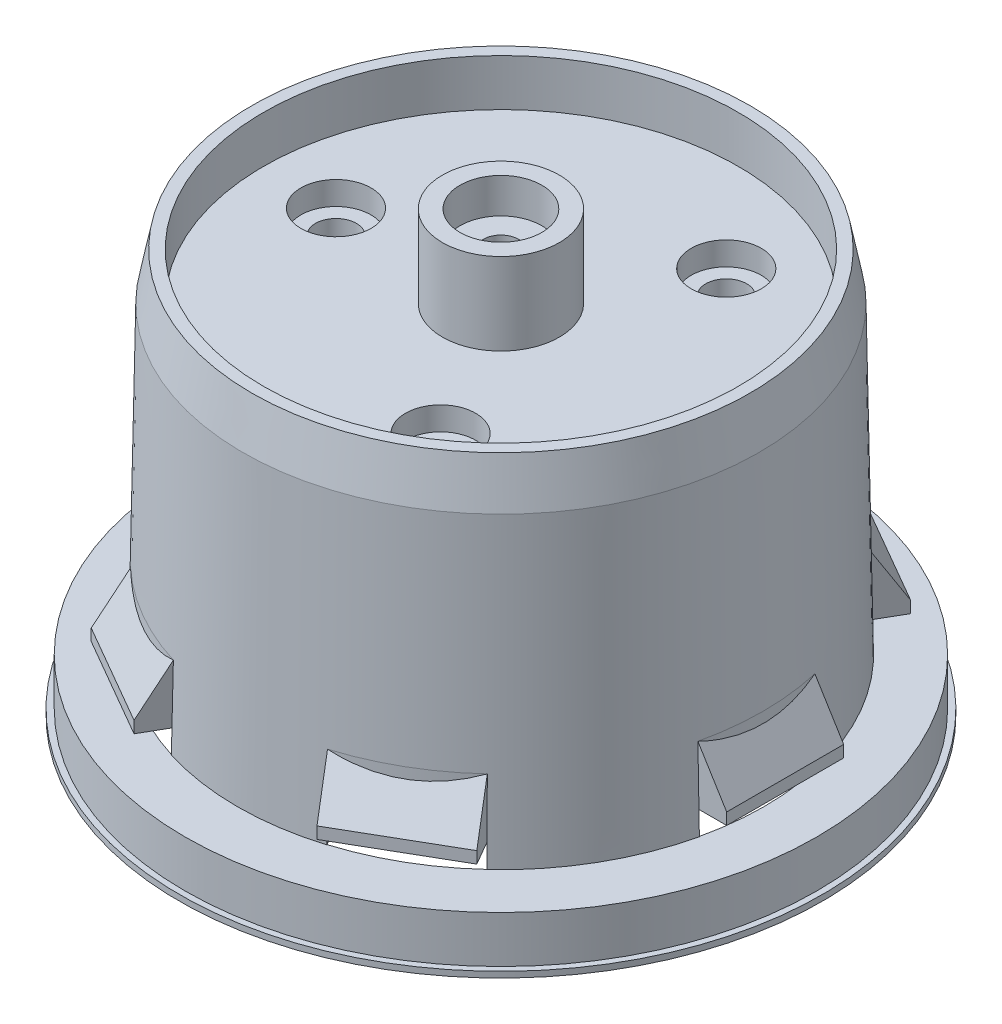
SolidWorks part; units mm, degrees
material "ABS PC"
ref_plane "Piano frontale" through (0, 0, 0) normal (0, 0, 1) x (1, 0, 0)
ref_plane "Piano superiore" through (0, 0, 0) normal (0, 1, 0) x (1, 0, 0)
ref_plane "Piano destro" through (0, 0, 0) normal (1, 0, 0) x (0, 0, -1)
sketch "Schizzo1" plane through (0, 0, 0) normal (0, 1, 0) x (1, 0, 0)
  circle A0 centre (0, 0) radius 22
  dimension "D1" = 44
extrude "Estrusione-Estrusione1" add sketch "Schizzo1" along normal blind 30
draft "Sformo1" type of draft neutral plane draft angle 1 faces to draft 1 face at (0, 30, 22) neutral plane through (0, 30, 0) neutral plane normal (0, 1, 0) parameters "D1"=1
chamfer "Smusso1" distance 4 angle 10 1 edges at (0, 30, 22)
sketch "Schizzo2" plane through (0, 30, 0) normal (0, 1, 0) x (1, 0, 0)
  circle A0 centre (0, 0) radius 20.2924
  circle A1 centre (0, 0) radius 21.2924 construction
  dimension "D1" = 1
extrude "Taglio-Estrusione1" cut sketch "Schizzo2" against normal blind 4
shell "Svuota1" thickness 3
sketch "Schizzo4" plane through (0, 26, 0) normal (0, 1, 0) x (1, 0, 0)
  line L0 (-17.5737, 10.1462) -> (17.5737, -10.1462) construction
  line L1 (17.5737, 10.1462) -> (-17.5737, -10.1462) construction
  line L2 (0, -20.2924) -> (0, 20.2924) construction
  line L3 (0, 0) -> (10.1462, 17.5737) construction
  circle A0 centre (0, 0) radius 20.2924 construction
  circle A1 centre (0, 0) radius 20.2924 construction
  circle A3 centre (7.05, 12.211) radius 3
  point P7 (0, 0)
  point P13 (0, 0)
  point P17 (0, 0)
  dimension "D5" = 6
  dimension "D1" = 60
  dimension "D2" = 60
  dimension "D3" = 30
  dimension "D4" = 14.1
extrude "Taglio-Estrusione2" cut sketch "Schizzo4" against normal blind 2
sketch "Schizzo5" plane through (0, 24, 0) normal (0, 1, 0) x (1, 0, 0)
  circle A0 centre (7.05, 12.211) radius 1.75
  dimension "D1" = 3.5
extrude "Taglio-Estrusione3" cut sketch "Schizzo5" against normal through all
pattern_circular "RipetizioneCircolare1" count 3 over 360 about axis through (0, 0, 0) along (0, 1, 0) of "Taglio-Estrusione3", "Taglio-Estrusione2"
sketch "Schizzo3" plane through (0, 26, 0) normal (0, 1, 0) x (1, 0, 0)
  circle A0 centre (0, 0) radius 5
  dimension "D1" = 10
extrude "Estrusione-Estrusione2" add sketch "Schizzo3" along normal blind 7
sketch "Schizzo6" plane through (0, 33, 0) normal (0, 1, 0) x (1, 0, 0)
  circle A0 centre (0, 0) radius 3.5
  dimension "D1" = 7
extrude "Taglio-Estrusione5" cut sketch "Schizzo6" against normal blind 3
sketch "Schizzo8" plane through (0, 23, 0) normal (0, -1, 0) x (1, 0, 0)
  line L0 (-17.5737, -10.1462) -> (17.5737, 10.1462) construction
  line L1 (0, 20.2924) -> (0, -20.2924) construction
  line L2 (17.5737, -10.1462) -> (-17.5737, 10.1462) construction
  line L3 (-17.5737, -10.1462) -> (17.5737, 10.1462)
  line L4 (0, 20.2924) -> (0, -20.2924)
  line L5 (17.5737, -10.1462) -> (-17.5737, 10.1462)
extrude "Estrusione-Sottile1" add sketch "Schizzo8" along normal blind 8 thin thin type mid plane wall 1
sketch "Schizzo7" plane through (0, 30, 0) normal (0, 1, 0) x (1, 0, 0)
  circle A0 centre (0, 0) radius 2.5
  circle A1 centre (0, 0) radius 1.5
  dimension "D1" = 5
  dimension "D2" = 3
extrude "Estrusione-Estrusione5" add sketch "Schizzo7" against normal offset from surface (17 mm away) 2 up to face at (0, 15, 0) offset beyond the face yes
sketch "Schizzo10" plane through (0, 30, 0) normal (0, 1, 0) x (1, 0, 0)
  circle A0 centre (0, 0) radius 1.5 construction
  circle A1 centre (0, 0) radius 1.5
extrude "Taglio-Estrusione7" cut sketch "Schizzo10" against normal through all
sketch "Schizzo11" plane through (0, 15, 0) normal (0, -1, 0) x (1, 0, 0)
  line L1 (-0.5, -2.4495) -> (-0.5, -19.2549) construction
  line L2 (0.5, -2.4495) -> (0.5, -19.1152) construction
  line L4 (0.5, -2.4495) -> (0.5, -19.2549) construction
  line L5 (-0.5, -10.8522) -> (0.5, -10.8522) construction
  line L6 (-0.5, -2.4495) -> (-0.5, -19.1152) construction
  circle A0 centre (0, -10.8522) radius 0.75
  point P2 (0.5, -10.8522)
  point P4 (-0.5, -10.8522)
  dimension "D1" = 1.5
extrude "Estrusione-Estrusione6" add sketch "Schizzo11" against normal up to surface (8 mm away) up to face at (-5.0997, 23, -8.8329)
pattern_circular "RipetizioneCircolare2" count 6 over 360 about axis through (0, 0, 0) along (0, 1, 0) of "Estrusione-Estrusione6"
sketch "Schizzo12" plane through (0, 23, 0) normal (0, -1, 0) x (1, 0, 0)
  circle A0 centre (7.05, -12.211) radius 3.5
  circle A1 centre (7.05, -12.211) radius 1.75 construction
  circle A2 centre (7.05, -12.211) radius 1.75
  dimension "D1" = 7
extrude "Estrusione-Estrusione7" add sketch "Schizzo12" along normal blind 5
sketch "Schizzo13" plane through (0, 18, 0) normal (0, -1, 0) x (1, 0, 0)
  circle A0 centre (7.05, -12.211) radius 3
  circle A1 centre (7.05, -12.211) radius 3.5 construction
  dimension "D1" = 0.5
extrude "Taglio-Estrusione8" cut sketch "Schizzo13" against normal blind 1.5
pattern_circular "RipetizioneCircolare3" count 3 over 360 about axis through (0, 0, 0) along (0, 1, 0) of "Taglio-Estrusione8", "Estrusione-Estrusione7"
sketch "Schizzo14" plane through (0, 0, 0) normal (0, -1, 0) x (1, 0, 0)
  circle A0 centre (0, 0) radius 27
  circle A1 centre (0, 0) radius 22.5
  dimension "D1" = 54
  dimension "D2" = 45
extrude "Estrusione-Estrusione8" add sketch "Schizzo14" along normal blind 4
sketch "Schizzo16" plane through (0, -4, 0) normal (0, -1, 0) x (1, 0, 0)
  circle A0 centre (0, 0) radius 27.5
  circle A1 centre (0, 0) radius 26.5
  dimension "D1" = 53
  dimension "D2" = 55
extrude "Estrusione-Estrusione9" add sketch "Schizzo16" along normal blind 0.5
ref_plane "Piano1" through (11.1484, 0, -19.3095) normal (0.5, 0, -0.866) x (0, 1, 0)
sketch "Schizzo17" plane through (11.1484, 0, -19.3095) normal (0.5, 0, -0.866) x (0, 1, 0)
  line L0 (0, -27) -> (0, 27) construction
  line L1 (0, -5) -> (2, -5)
  line L2 (0, -5) -> (0, 5)
  line L3 (0, 5) -> (2, 5)
  line L4 (2, -5) -> (2, 5)
  dimension "D1" = 10
  dimension "D2" = 2
extrude "Taglio-Estrusione9" cut sketch "Schizzo17" against normal mid plane 8
sketch "Schizzo18" plane through (11.1484, 0, -19.3095) normal (0.5, 0, -0.866) x (0, 1, 0)
  line L0 (2, -5) -> (0, -5) construction
  line L1 (2, 5) -> (7, 5)
  line L2 (2, 5) -> (2, -5)
  line L3 (2, -5) -> (7, -5)
  line L4 (7, 5) -> (7, -5)
  dimension "D1" = 5
extrude "Estrusione-Estrusione10" add sketch "Schizzo18" along normal mid plane 4
sketch "Schizzo19" plane through (-4.3301, 0, -2.5) normal (-0.866, 0, -0.5) x (-0.5, 0, 0.866)
  line L0 (-21.8363, 7) -> (-24.2967, 3)
  line L1 (-24.2967, 2) -> (-24.2967, 7) construction
  line L2 (-24.2967, 3) -> (-24.2967, 7)
  line L3 (-24.2967, 7) -> (-21.8363, 7)
  line L4 (-24.2967, 2) -> (-21.9259, 2) construction
  line L5 (-24.2967, 7) -> (-21.8363, 7) construction
  line L6 (-21.9259, 2) -> (-21.8363, 7) construction
  dimension "D1" = 1
extrude "Taglio-Estrusione10" cut sketch "Schizzo19" against normal blind 10
sketch "Schizzo20" plane through (0, 7, 0) normal (0, -1, 0) x (1, 0, 0)
  line L1 (15.2483, -16.4108) -> (6.588, -21.4108)
  line L2 (15.2483, -16.4108) -> (6.588, -21.4108)
  arc A1 (6.588, -21.4108) -> (15.2483, -16.4108) centre (0, 0) ccw
  arc A2 (6.588, -21.4108) -> (15.2483, -16.4108) centre (0, 0) ccw
  dimension "D1" = 0
extrude "Estrusione-Estrusione11" add sketch "Schizzo20" along normal blind 1
pattern_circular "RipetizioneCircolare11" count 6 over 360 about axis through (0, 0, 0) along (0, 1, 0) of "Estrusione-Estrusione10", "Taglio-Estrusione9", "Taglio-Estrusione10", "Estrusione-Estrusione11"
move or copy body "Corpo-Sposta/copia1" [suppressed]
